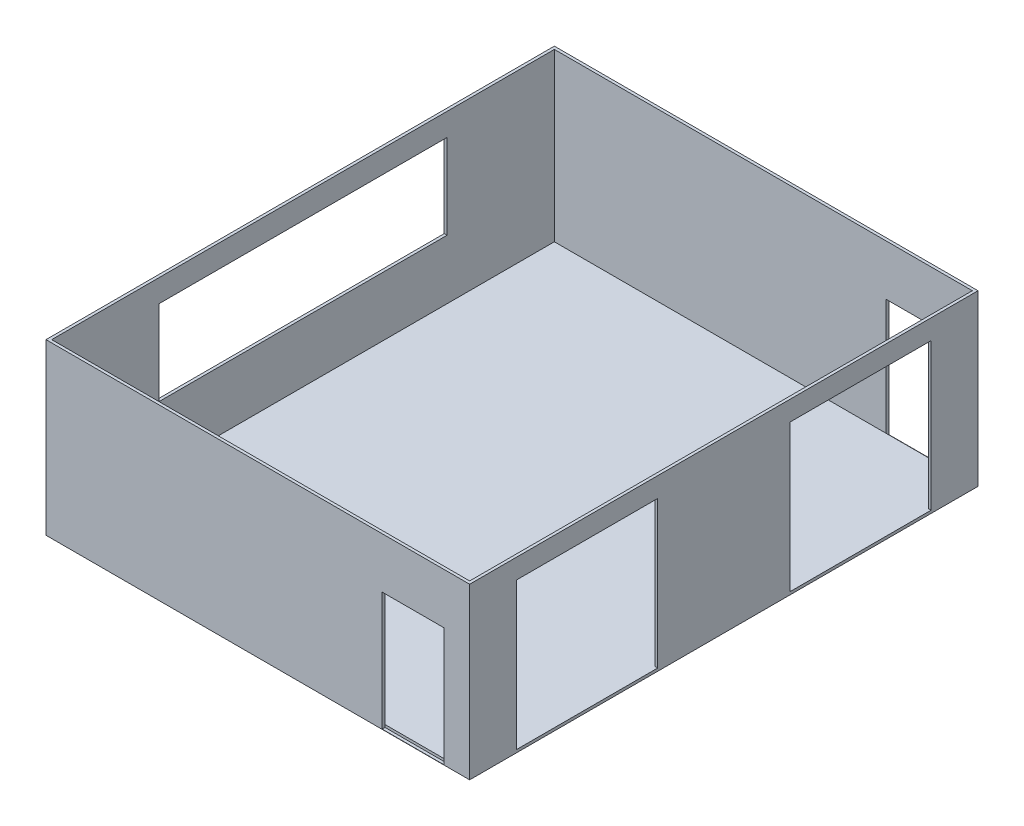
SolidWorks part; units mm, degrees
ref_plane "Front Plane" through (0, 0, 0) normal (0, 0, 1) x (1, 0, 0)
ref_plane "Top Plane" through (0, 0, 0) normal (0, 1, 0) x (1, 0, 0)
ref_plane "Right Plane" through (0, 0, 0) normal (1, 0, 0) x (0, 0, -1)
sketch "Sketch1" plane through (0, 0, 0) normal (0, 1, 0) x (1, 0, 0)
  line L1 (3750, -4500) -> (-3750, -4500)
  line L2 (3750, -4500) -> (3750, 4500)
  line L3 (3750, 4500) -> (-3750, 4500)
  line L4 (-3750, -4500) -> (-3750, 4500)
  line L5 (3750, -4500) -> (-3750, 4500) construction
  line L6 (3750, 4500) -> (-3750, -4500) construction
  point P0 (0, 0)
  dimension "D1" = 9000
  dimension "D2" = 7500
extrude "Boss-Extrude1" add sketch "Sketch1" along normal blind 3000
shell "Shell1" thickness 50
sketch "Sketch2" plane through (3750, 0, 0) normal (1, 0, 0) x (0, 0, -1)
  line L0 (-4500, 0) -> (4500, 0) construction
  line L1 (3670, 2650) -> (1170, 2650)
  line L2 (3670, 2650) -> (3670, 50)
  line L3 (3670, 50) -> (1170, 50)
  line L4 (1170, 2650) -> (1170, 50)
  line L5 (3670, 2650) -> (1170, 50) construction
  line L6 (3670, 50) -> (1170, 2650) construction
  line L7 (4500, 3000) -> (4500, 0) construction
  point P4 (2420, 1350)
  dimension "D1" = 50
  dimension "D2" = 830
  dimension "D3" = 2600
  dimension "D4" = 2500
extrude "Cut-Extrude2" cut sketch "Sketch2" against normal up to next
sketch "Sketch3" plane through (3750, 0, 0) normal (1, 0, 0) x (0, 0, -1)
  line L0 (-4500, 3000) -> (-4500, 0) construction
  line L1 (-1170, 2650) -> (-3670, 2650)
  line L2 (-1170, 2650) -> (-1170, 50)
  line L3 (-1170, 50) -> (-3670, 50)
  line L4 (-3670, 2650) -> (-3670, 50)
  line L5 (-1170, 2650) -> (-3670, 50) construction
  line L6 (-1170, 50) -> (-3670, 2650) construction
  line L7 (-4500, 0) -> (4500, 0) construction
  point P4 (-2420, 1350)
  dimension "D1" = 830
  dimension "D2" = 50
  dimension "D3" = 2600
  dimension "D4" = 2500
extrude "Cut-Extrude3" cut sketch "Sketch3" against normal blind 3000
sketch "Sketch4" plane through (0, 0, 4500) normal (0, 0, 1) x (1, 0, 0)
  line L1 (3300, 2105) -> (2200, 2105)
  line L2 (3300, 2105) -> (3300, 5)
  line L3 (3300, 5) -> (2200, 5)
  line L4 (2200, 2105) -> (2200, 5)
  line L5 (3300, 2105) -> (2200, 5) construction
  line L6 (3300, 5) -> (2200, 2105) construction
  line L7 (3750, 3000) -> (3750, 0) construction
  line L8 (-3750, 0) -> (3750, 0) construction
  point P4 (2750, 1055)
  dimension "D1" = 1100
  dimension "D2" = 2100
  dimension "D3" = 2105
  dimension "D4" = 450
extrude "Cut-Extrude4" cut sketch "Sketch4" against normal blind 50
sketch "Sketch6" plane through (0, 0, -4500) normal (0, 0, -1) x (-1, 0, 0)
  line L0 (-3750, 3000) -> (-3750, 0) construction
  line L1 (-3270, 5) -> (-2170, 5)
  line L2 (-3270, 5) -> (-3270, 2105)
  line L3 (-3270, 2105) -> (-2170, 2105)
  line L4 (-2170, 5) -> (-2170, 2105)
  line L5 (-3270, 5) -> (-2170, 2105) construction
  line L6 (-3270, 2105) -> (-2170, 5) construction
  line L7 (-3750, 0) -> (3750, 0) construction
  point P4 (-2720, 1055)
  dimension "D1" = 480
  dimension "D2" = 1100
  dimension "D3" = 2100
  dimension "D4" = 2105
extrude "Cut-Extrude5" cut sketch "Sketch6" against normal blind 50
sketch "Sketch7" plane through (-3750, 0, 0) normal (-1, 0, 0) x (0, 0, 1)
  line L0 (0, 0) -> (0, 3000) construction
  line L1 (-2550, 2600) -> (2550, 2600)
  line L2 (-2550, 2600) -> (-2550, 1100)
  line L3 (-2550, 1100) -> (2550, 1100)
  line L4 (2550, 2600) -> (2550, 1100)
  line L5 (-2550, 2600) -> (2550, 1100) construction
  line L6 (-2550, 1100) -> (2550, 2600) construction
  line L8 (2550, 2600) -> (2550, 1100)
  line L11 (-4500, 0) -> (4500, 0) construction
  line L12 (-4500, 3000) -> (4500, 3000) construction
  point P4 (0, 1850)
  point P11 (0, 1819.1535)
  dimension "D1" = 5100
  dimension "D2" = 1500
  dimension "D3" = 400
extrude "Cut-Extrude6" cut sketch "Sketch7" against normal blind 50 contours L4 L1 L2 L3
